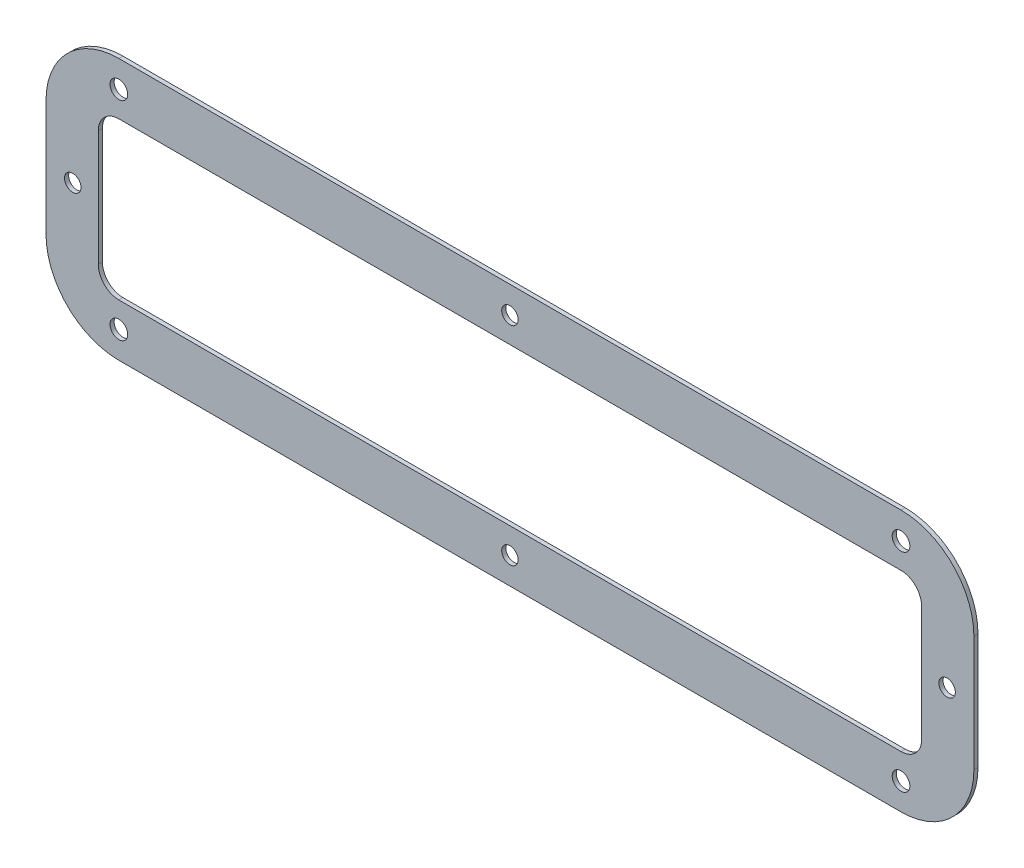
SolidWorks part; units mm, degrees
ref_plane "Plan de face" through (0, 0, 0) normal (0, 0, 1) x (1, 0, 0)
ref_plane "Plan de dessus" through (0, 0, 0) normal (0, 1, 0) x (1, 0, 0)
ref_plane "Plan de droite" through (0, 0, 0) normal (1, 0, 0) x (0, 0, -1)
sketch "Esquisse1" plane through (0, 0, 0) normal (0, 0, 1) x (1, 0, 0)
  line L0 (0, 0) -> (-106.2, 0) construction
  line L1 (-95, -31.75) -> (95, -31.75)
  line L2 (-112.7, -14.05) -> (-112.7, 14.05)
  line L3 (-95, 31.75) -> (95, 31.75)
  line L4 (112.7, -14.05) -> (112.7, 14.05)
  line L5 (-112.7, -31.75) -> (112.7, 31.75) construction
  line L6 (-112.7, 31.75) -> (112.7, -31.75) construction
  line L7 (-95, -19.05) -> (95, -19.05)
  line L8 (-100, -14.05) -> (-100, 14.05)
  line L9 (-95, 19.05) -> (95, 19.05)
  line L10 (100, -14.05) -> (100, 14.05)
  line L11 (-100, -19.05) -> (100, 19.05) construction
  line L12 (-100, 19.05) -> (100, -19.05) construction
  line L13 (0, 0) -> (0, -25.25) construction
  arc A0 (95, 31.75) -> (112.7, 14.05) centre (95, 14.05) cw
  arc A1 (95, -31.75) -> (112.7, -14.05) centre (95, -14.05) ccw
  arc A2 (-95, -31.75) -> (-112.7, -14.05) centre (-95, -14.05) cw
  arc A3 (-112.7, 14.05) -> (-95, 31.75) centre (-95, 14.05) cw
  arc A4 (95, 19.05) -> (100, 14.05) centre (95, 14.05) cw
  arc A5 (95, -19.05) -> (100, -14.05) centre (95, -14.05) ccw
  arc A6 (-95, -19.05) -> (-100, -14.05) centre (-95, -14.05) cw
  arc A7 (-100, 14.05) -> (-95, 19.05) centre (-95, 14.05) cw
  circle A8 centre (-106.2, 0) radius 2
  circle A9 centre (0, 25.25) radius 2
  circle A10 centre (-95, 25.25) radius 2.1469
  circle A11 centre (-95, -25.25) radius 2.1469
  circle A12 centre (0, -25.25) radius 2
  circle A13 centre (95, -25.25) radius 2.1469
  circle A14 centre (106.2, 0) radius 2
  circle A15 centre (95, 25.25) radius 2.1469
  point P0 (0, 0)
  point P18 (0, 0)
  dimension "D3" = 17.7
  dimension "D6" = 5
  dimension "D8" = 4
  dimension "D10" = 4
  dimension "D1" = 225.4
  dimension "D2" = 63.5
  dimension "D4" = 200
  dimension "D5" = 38.1
  dimension "D7" = 6.5
  dimension "D9" = 6.5
  dimension "D11" = 95
  dimension "D12" = 6.5
extrude "Boss.-Extru.1" add sketch "Esquisse1" along normal blind 1
